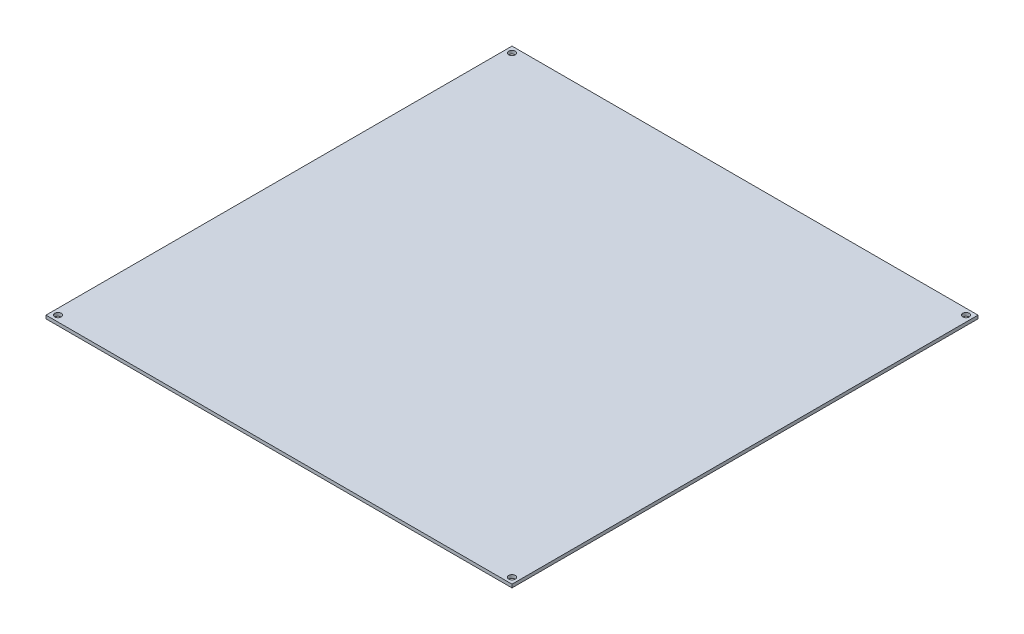
SolidWorks part; units mm, degrees
material "ABS"
ref_plane "Plano frontal" through (0, 0, 0) normal (0, 0, 1) x (1, 0, 0)
ref_plane "Plano superior" through (0, 0, 0) normal (0, 1, 0) x (1, 0, 0)
ref_plane "Plano direito" through (0, 0, 0) normal (1, 0, 0) x (0, 0, -1)
sketch "Esboço1" plane through (0, 0, 0) normal (0, 1, 0) x (1, 0, 0)
  line L0 (0, 0) -> (0, 107) construction
  line L1 (-107, 107) -> (107, 107)
  line L2 (-107, 107) -> (-107, -107)
  line L3 (-107, -107) -> (107, -107)
  line L4 (107, 107) -> (107, -107)
  line L5 (-107, 107) -> (107, -107) construction
  line L6 (-107, -107) -> (107, 107) construction
  line L7 (0, 0) -> (107, 0) construction
  circle A0 centre (104.25, 104.25) radius 1.5
  circle A1 centre (-104.25, 104.25) radius 1.5
  circle A2 centre (104.25, -104.25) radius 1.5
  circle A3 centre (-104.25, -104.25) radius 1.5
  point P0 (0, 0)
  dimension "D2" = 3
  dimension "D3" = 208.5
  dimension "D1" = 214
extrude "Ressalto-extrusão1" add sketch "Esboço1" along normal mid plane 1.5
